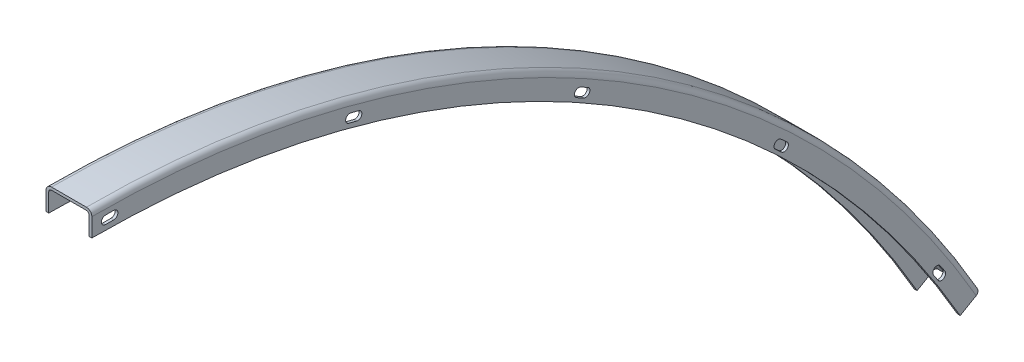
SolidWorks part; units mm, degrees
material "ASTM A36 Steel"
ref_plane "Front Plane" through (0, 0, 0) normal (0, 0, 1) x (1, 0, 0)
ref_plane "Top Plane" through (0, 0, 0) normal (0, 1, 0) x (1, 0, 0)
ref_plane "Right Plane" through (0, 0, 0) normal (1, 0, 0) x (0, 0, -1)
sketch "Sketch1" plane through (0, 0, 0) normal (0, 0, 1) x (1, 0, 0)
  line L0 (6.8425, 105.3307) -> (-44.1575, 105.3307)
  line L1 (-52.1575, 97.3307) -> (-52.1575, 70.3307)
  line L2 (-52.1575, 70.3307) -> (-48.1575, 70.3307)
  line L3 (-48.1575, 70.3307) -> (-48.1575, 97.3307)
  line L4 (-44.1575, 101.3307) -> (6.8425, 101.3307)
  line L5 (10.8425, 97.3307) -> (10.8425, 70.3307)
  line L6 (10.8425, 70.3307) -> (14.8425, 70.3307)
  line L7 (14.8425, 70.3307) -> (14.8425, 97.3307)
  line L8 (14.8425, -1394.6693) -> (-71.0301, -1394.6693)
  arc A0 (-48.1575, 97.3307) -> (-44.1575, 101.3307) centre (-44.1575, 97.3307) cw
  arc A1 (10.8425, 97.3307) -> (6.8425, 101.3307) centre (6.8425, 97.3307) ccw
  arc A2 (14.8425, 97.3307) -> (6.8425, 105.3307) centre (6.8425, 97.3307) ccw
  arc A3 (-52.1575, 97.3307) -> (-44.1575, 105.3307) centre (-44.1575, 97.3307) cw
  point P14 (14.8425, 105.3307)
  point P17 (-52.1575, 105.3307)
  dimension "D7" = 4
  dimension "D8" = 8
  dimension "D1" = 67
  dimension "D2" = 35
  dimension "D3" = 35
  dimension "D4" = 4
  dimension "D5" = 4
  dimension "D6" = 4
  dimension "D9" = 1500
revolve "Revolve1" add sketch "Sketch1" angle 60 about L8
sketch "Sketch2" plane through (14.8425, 0, 0) normal (1, 0, 0) x (0, 0, -1)
  line L0 (20, 83.3307) -> (32, 83.3307) construction
  line L1 (20, 89.3307) -> (32, 89.3307)
  line L2 (20, 77.3307) -> (32, 77.3307)
  line L3 (376.8375, 33.6054) -> (388.4811, 30.7024) construction
  line L4 (378.2891, 39.4272) -> (389.9326, 36.5242)
  line L5 (375.386, 27.7837) -> (387.0295, 24.8806)
  line L6 (711.0458, -100.9696) -> (721.6412, -106.6032) construction
  line L7 (713.8627, -95.6719) -> (724.458, -101.3055)
  line L8 (708.229, -106.2673) -> (718.8244, -111.9009)
  line L9 (1002.7701, -312.3994) -> (1011.6878, -320.429) construction
  line L10 (1006.7848, -307.9406) -> (1015.7026, -315.9701)
  line L11 (998.7553, -316.8583) -> (1007.673, -324.8879)
  line L12 (1234.6793, -588.1234) -> (1241.3896, -598.0719) construction
  line L13 (1239.6536, -584.7683) -> (1246.3639, -594.7167)
  line L14 (1229.7051, -591.4786) -> (1236.4154, -601.427)
  line L15 (-4.0711, -1394.6361) -> (20, 83.3307) construction
  line L16 (-4.0711, -1394.6361) -> (376.8375, 33.6054) construction
  line L17 (1392.9962, -911.7612) -> (1397.1005, -923.0375) construction
  line L18 (1398.6344, -909.709) -> (1402.7386, -920.9854)
  line L19 (1387.3581, -913.8133) -> (1391.4623, -925.0896)
  arc A0 (20, 89.3307) -> (20, 77.3307) centre (20, 83.3307) ccw
  arc A1 (32, 77.3307) -> (32, 89.3307) centre (32, 83.3307) ccw
  arc A2 (1398.6344, -909.709) -> (1387.3581, -913.8133) centre (1392.9962, -911.7612) ccw
  arc A3 (378.2891, 39.4272) -> (375.386, 27.7837) centre (376.8375, 33.6054) ccw
  arc A4 (387.0295, 24.8806) -> (389.9326, 36.5242) centre (388.4811, 30.7024) ccw
  arc A5 (713.8627, -95.6719) -> (708.229, -106.2673) centre (711.0458, -100.9696) ccw
  arc A6 (718.8244, -111.9009) -> (724.458, -101.3055) centre (721.6412, -106.6032) ccw
  arc A7 (1006.7848, -307.9406) -> (998.7553, -316.8583) centre (1002.7701, -312.3994) ccw
  arc A8 (1007.673, -324.8879) -> (1015.7026, -315.9701) centre (1011.6878, -320.429) ccw
  arc A9 (1239.6536, -584.7683) -> (1229.7051, -591.4786) centre (1234.6793, -588.1234) ccw
  arc A10 (1236.4154, -601.427) -> (1246.3639, -594.7167) centre (1241.3896, -598.0719) ccw
  arc A11 (1391.4623, -925.0896) -> (1402.7386, -920.9854) centre (1397.1005, -923.0375) ccw
  point P2 (26, 83.3307)
  point P9 (1395.0484, -917.3993)
  point P12 (382.6593, 32.1539)
  point P15 (1162.974, -744.2252)
  point P20 (716.3435, -103.7864)
  point P28 (1007.2289, -316.4142)
  point P35 (1238.0345, -593.0977)
  dimension "D1" = 13
  dimension "D2" = 20
  dimension "D3" = 12
  dimension "D4" = 6
  dimension "D5" = 14
  dimension "D6" = 1478.1629
extrude "Cut-Extrude1" cut sketch "Sketch2" against normal blind 10
